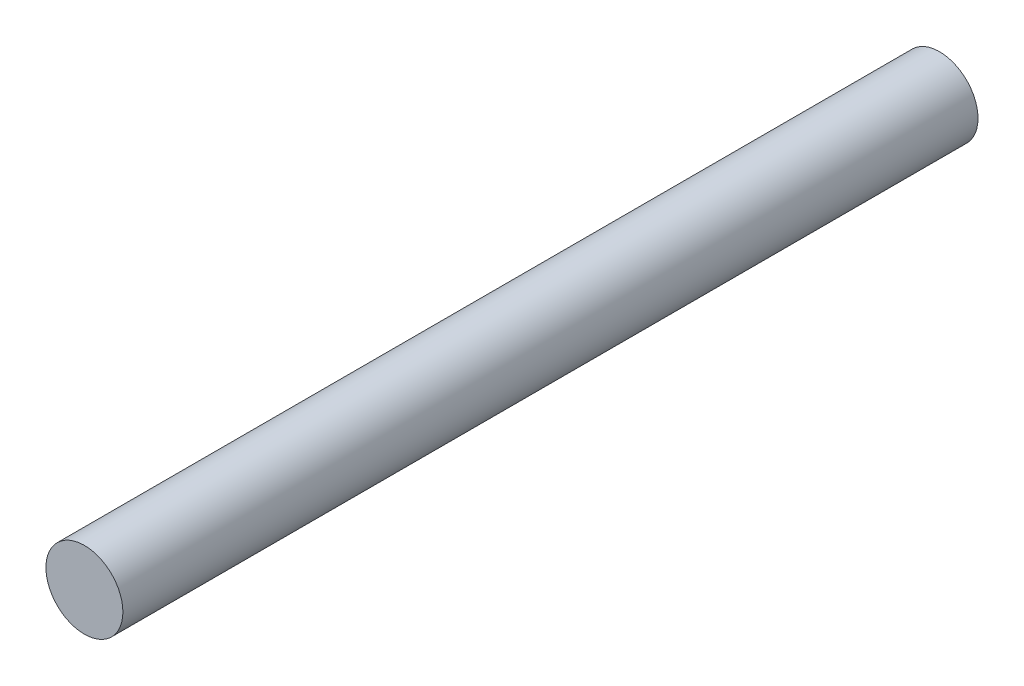
SolidWorks part; units mm, degrees
ref_plane "Plano frontal" through (0, 0, 0) normal (0, 0, 1) x (1, 0, 0)
ref_plane "Plano superior" through (0, 0, 0) normal (0, 1, 0) x (1, 0, 0)
ref_plane "Plano direito" through (0, 0, 0) normal (1, 0, 0) x (0, 0, -1)
sketch "Esboço1" plane through (0, 0, 0) normal (0, 0, 1) x (1, 0, 0)
  circle A0 centre (0, 0) radius 2.7
  dimension "D1" = 5.4
extrude "Ressalto-extrusão1" add sketch "Esboço1" along normal blind 60
